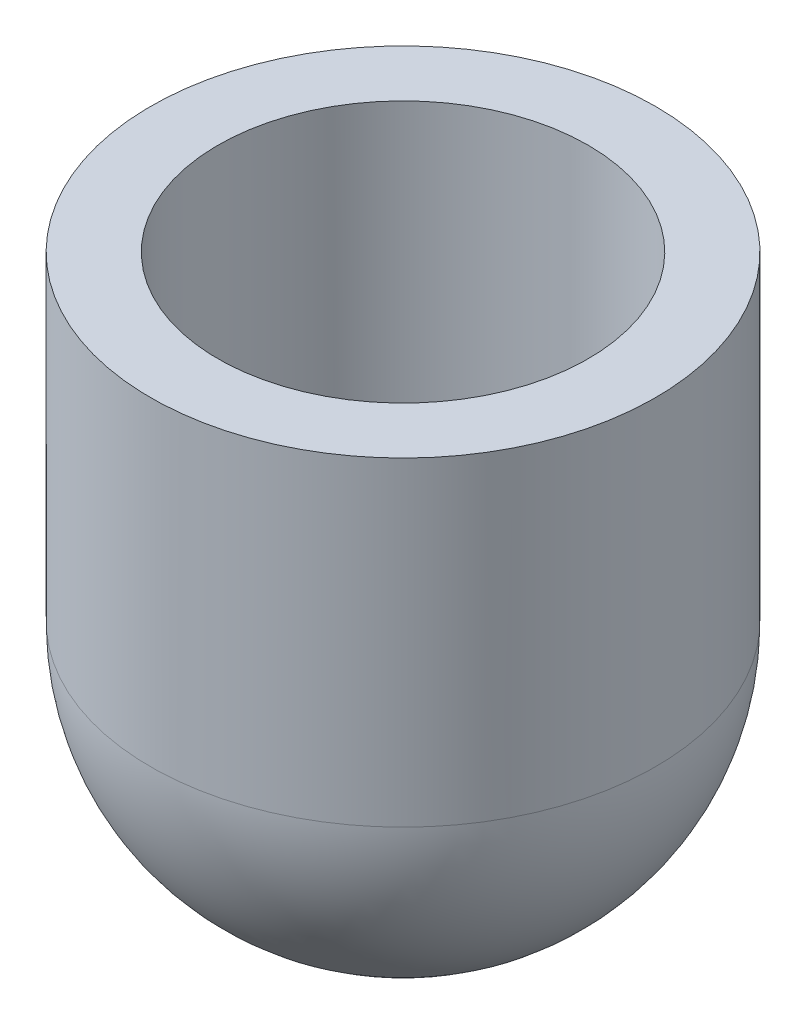
SolidWorks part; units mm, degrees
material "Silicon Rubber"
ref_plane "Front Plane" through (0, 0, 0) normal (0, 0, 1) x (1, 0, 0)
ref_plane "Top Plane" through (0, 0, 0) normal (0, 1, 0) x (1, 0, 0)
ref_plane "Right Plane" through (0, 0, 0) normal (1, 0, 0) x (0, 0, -1)
sketch "Sketch1" plane through (0, 0, 0) normal (0, 0, 1) x (1, 0, 0)
  line L0 (-7.5, 0) -> (-7.5, -9.5)
  line L3 (-7.5, 0) -> (-5.5, 0)
  line L4 (-5.5, 0) -> (-5.5, -9.5)
  line L5 (0, -17) -> (0, -15)
  arc A0 (-7.5, -9.5) -> (0, -17) centre (0, -9.5) ccw
  arc A1 (-5.5, -9.5) -> (0, -15) centre (0, -9.5) ccw
  dimension "D1" = 7.5
  dimension "D3" = 9.5
  dimension "D2" = 5.5
revolve "Revolve1" add sketch "Sketch1" angle 360 about L5
